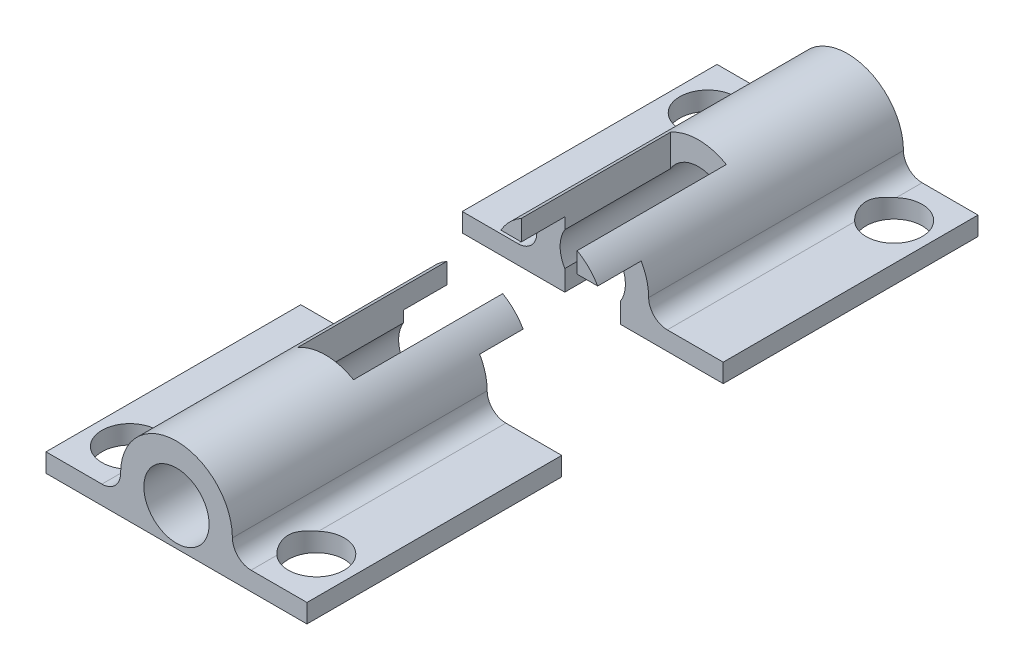
SolidWorks part; units mm, degrees
ref_plane "Ön Düzlem" through (0, 0, 0) normal (0, 0, 1) x (1, 0, 0)
ref_plane "Üst Düzlem" through (0, 0, 0) normal (0, 1, 0) x (1, 0, 0)
ref_plane "Sağ Düzlem" through (0, 0, 0) normal (1, 0, 0) x (0, 0, -1)
sketch "Çizim1" plane through (0, 0, 0) normal (0, 0, 1) x (1, 0, 0)
  line L9 (-7, -2) -> (-7, -1)
  line L11 (7, -2) -> (7, -1)
  line L12 (-7, -2) -> (7, -2)
  line L13 (-7, -1) -> (-2.8284, -1)
  line L14 (7, -1) -> (2.8284, -1)
  circle A1 centre (0, 0) radius 1.75
  arc A2 (2.8284, -1) -> (-2.8284, -1) centre (0, 0) ccw
  dimension "D1" = 3.5
  dimension "D2" = 3
  dimension "D3" = 2
  dimension "D4" = 14
  dimension "D5" = 1
  dimension "D6" = 7
extrude "Yükseklik-Ekstrüzyon1" add sketch "Çizim1" along normal mid plane 36
fillet "Radyus1" radius 1 2 edges at (2.8284, -1, 0) (-2.8284, -1, 0)
sketch "Çizim3" plane through (0, -1, 0) normal (0, 1, 0) x (1, 0, 0)
  line L0 (7, -18) -> (4, -18) construction
  line L1 (7, 18) -> (4, 18) construction
  circle A0 centre (-5, -15.5) radius 1.5
  circle A1 centre (5, -15.5) radius 1.5
  circle A2 centre (5, 15.5) radius 1.5
  circle A3 centre (-5, 15.5) radius 1.5
  dimension "D1" = 3
  dimension "D4" = 2.5
  dimension "D2" = 10
  dimension "D3" = 5
  dimension "D5" = 2.5
extrude "Kes-Ekstrüzyon3" cut sketch "Çizim3" against normal blind 10 and the other way blind 11
ref_plane "Düzlem1" through (0, -2, 0) normal (0, 1, 0) x (1, 0, 0)
sketch "Çizim5" plane through (0, -2, 0) normal (0, -1, 0) x (1, 0, 0)
  line L0 (0, -10) -> (0, 10)
  line L1 (0, -10) -> (-1.5, -10)
  line L2 (-1.5, -10) -> (-1.5, -2)
  line L3 (-1.5, -2) -> (-3.5, -2)
  line L4 (-3.5, -2) -> (-3.5, -4.3314)
  line L5 (-3.5, -4.3314) -> (-7, -4.3314)
  line L6 (-7, 18) -> (-7, -18) construction
  line L7 (1.5, -2) -> (3.5, -2)
  line L8 (3.5, -4.3314) -> (7, -4.3314)
  line L9 (3.5, -2) -> (3.5, -4.3314)
  line L10 (1.5, -10) -> (1.5, -2)
  line L11 (1.5, -10) -> (0, -10)
  line L12 (-6.7666, 0) -> (6.5218, 0) construction
  line L13 (1.5, 10) -> (0, 10)
  line L14 (0, 10) -> (-1.5, 10)
  line L15 (1.5, 2) -> (3.5, 2)
  line L16 (1.5, 10) -> (1.5, 2)
  line L17 (3.5, 2) -> (3.5, 4.3314)
  line L18 (3.5, 4.3314) -> (7, 4.3314)
  line L19 (-1.5, 2) -> (-3.5, 2)
  line L20 (-3.5, 4.3314) -> (-7, 4.3314)
  line L21 (-3.5, 2) -> (-3.5, 4.3314)
  line L22 (-1.5, 10) -> (-1.5, 2)
  line L23 (7, -4.3314) -> (7, 4.3314)
  line L24 (-7, -4.3314) -> (-7, 4.3314)
  dimension "D1" = 20
  dimension "D2" = 10
  dimension "D3" = 3.5
  dimension "D4" = 2
  dimension "D5" = 8
extrude "Kes-Ekstrüzyon4" cut sketch "Çizim5" against normal blind 10
sketch "Çizim6" plane through (-3.5, 0, 0) normal (-1, 0, 0) x (0, 0, 1)
  line L0 (7.7, -2) -> (-7.7, -2) construction
  line L1 (4.3314, 1.5) -> (-4.3314, 1.5)
  line L2 (4.3314, 1.5) -> (4.3314, -2)
  line L3 (4.3314, -2) -> (-4.3314, -2)
  line L4 (-4.3314, 1.5) -> (-4.3314, -2)
  line L5 (4.3314, 1.5) -> (-4.3314, -2) construction
  line L6 (4.3314, -2) -> (-4.3314, 1.5) construction
  line L7 (-4.3314, -1) -> (-4.3314, -2) construction
  point P0 (0, -0.25)
  dimension "D1" = 3.5
extrude "Kes-Ekstrüzyon5" cut sketch "Çizim6" against normal blind 11 and the other way blind 13
